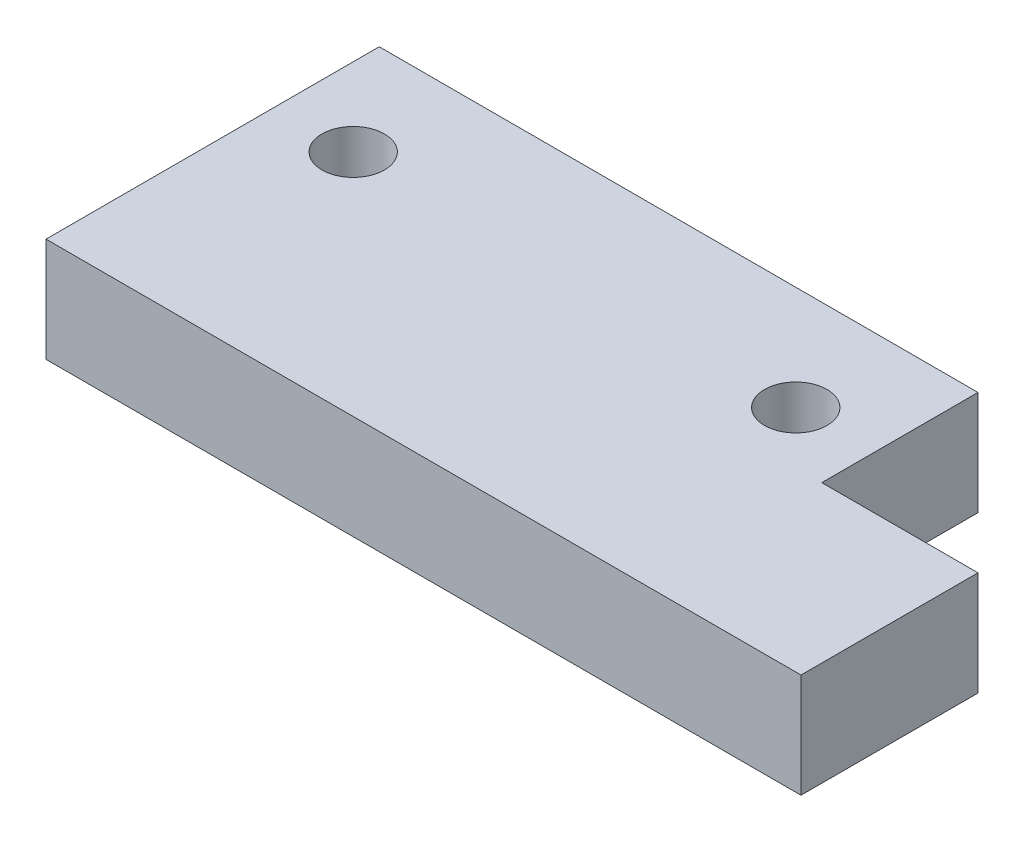
SolidWorks part; units mm, degrees
ref_plane "前基準面" through (0, 0, 0) normal (0, 0, 1) x (1, 0, 0)
ref_plane "上基準面" through (0, 0, 0) normal (0, 1, 0) x (1, 0, 0)
ref_plane "右基準面" through (0, 0, 0) normal (1, 0, 0) x (0, 0, -1)
sketch "草圖1" plane through (0, 0, 0) normal (0, 1, 0) x (1, 0, 0)
  line L1 (0, 0) -> (35, 0)
  line L2 (0, 0) -> (0, 20)
  line L3 (0, 20) -> (35, 20)
  line L4 (35, 0) -> (35, 20)
  dimension "D1" = 35
  dimension "D2" = 20
extrude "填料-伸長1" add sketch "草圖1" along normal blind 4
sketch "草圖3" plane through (0, 0, 0) normal (0, 1, 0) x (1, 0, 0)
  line L1 (6, 0) -> (35, 0)
  line L2 (6, 0) -> (6, 7.2)
  line L3 (6, 7.2) -> (35, 7.2)
  line L4 (35, 0) -> (35, 7.2)
  dimension "D1" = 29
  dimension "D2" = 7.2
extrude "除料-伸長4" cut sketch "草圖3" along normal blind 5
sketch "草圖4" plane through (0, 0, 0) normal (0, 1, 0) x (1, 0, 0)
  line L1 (35, 20) -> (29, 20)
  line L2 (35, 20) -> (35, 14)
  line L3 (35, 14) -> (29, 14)
  line L4 (29, 20) -> (29, 14)
  dimension "D1" = 6
  dimension "D2" = 6
extrude "除料-伸長5" cut sketch "草圖4" along normal blind 5
sketch "草圖5" plane through (0, 0, 0) normal (0, 1, 0) x (1, 0, 0)
  circle A0 centre (3, 16) radius 1.2
  circle A1 centre (3, 4) radius 1.2
  circle A2 centre (9, 16) radius 1.2
  circle A4 centre (26, 16) radius 1.2
extrude "除料-伸長6" cut sketch "草圖5" along normal through all
sketch "草圖6" plane through (0, 0, 0) normal (0, 1, 0) x (1, 0, 0)
  circle A1 centre (3, 16) radius 2.2
  circle A2 centre (3, 4) radius 2.2
extrude "除料-伸長7" cut sketch "草圖6" along normal blind 2
sketch "草圖7" plane through (0, 0, 0) normal (0, 1, 0) x (1, 0, 0)
  circle A0 centre (9, 16) radius 2.2
  circle A1 centre (26, 16) radius 2.2
extrude "除料-伸長8" cut sketch "草圖7" against normal blind 2 from surface at 4 starting at face at (9, 4, -14.8)
mirror "鏡射1" about plane through (0, 0, 0) normal (0, 1, 0) of "除料-伸長8", "除料-伸長7", "除料-伸長5", "除料-伸長4", "填料-伸長1", "除料-伸長6"
sketch "草圖8" plane through (0, 0, 0) normal (0, 1, 0) x (1, 0, 0)
  line L1 (-1.3087, 21.0021) -> (38.9593, 21.0021)
  line L2 (-1.3087, 21.0021) -> (-1.3087, -3.7525)
  line L3 (-1.3087, -3.7525) -> (38.9593, -3.7525)
  line L4 (38.9593, 21.0021) -> (38.9593, -3.7525)
extrude "除料-伸長9" cut sketch "草圖8" along normal through all
sketch "草圖11" plane through (0, 0, 0) normal (0, 1, 0) x (1, 0, 0)
  line L1 (6, 0) -> (0, 0)
  line L2 (6, 0) -> (6, 20)
  line L3 (6, 20) -> (0, 20)
  line L4 (0, 0) -> (0, 20)
extrude "除料-伸長11" cut sketch "草圖11" against normal through all
